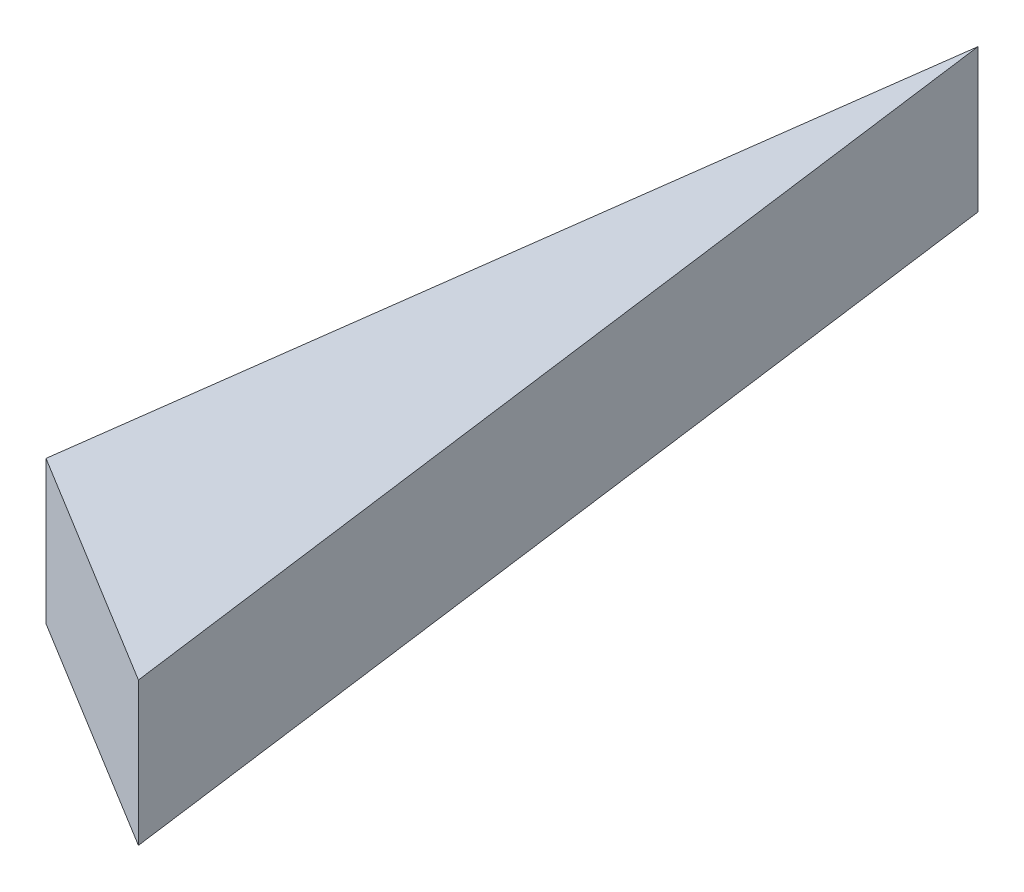
SolidWorks part; units mm, degrees
material "AISI 4340 Steel, annealed"
ref_plane "Front Plane" through (0, 0, 0) normal (0, 0, 1) x (1, 0, 0)
ref_plane "Top Plane" through (0, 0, 0) normal (0, 1, 0) x (1, 0, 0)
ref_plane "Right Plane" through (0, 0, 0) normal (1, 0, 0) x (0, 0, -1)
sketch "Sketch1" plane through (0, 0, 0) normal (0, 1, 0) x (1, 0, 0)
  line L0 (0, 0) -> (-99.4384, -747.7572)
  line L1 (-117.055, -880.231) -> (117.055, -880.231) construction
  line L2 (117.055, -880.231) -> (0, 0)
  line L3 (-99.4384, -747.7572) -> (117.055, -880.231)
  line L4 (-99.4384, -747.7572) -> (-117.055, -880.231) construction
  point P3 (0, -880.231)
  dimension "D1" = 887.98
  dimension "D2" = 234.11
  dimension "D3" = 133.64
extrude "Main extrude" add sketch "Sketch1" along normal mid plane 130.18
shell "Shell1" thickness 5
